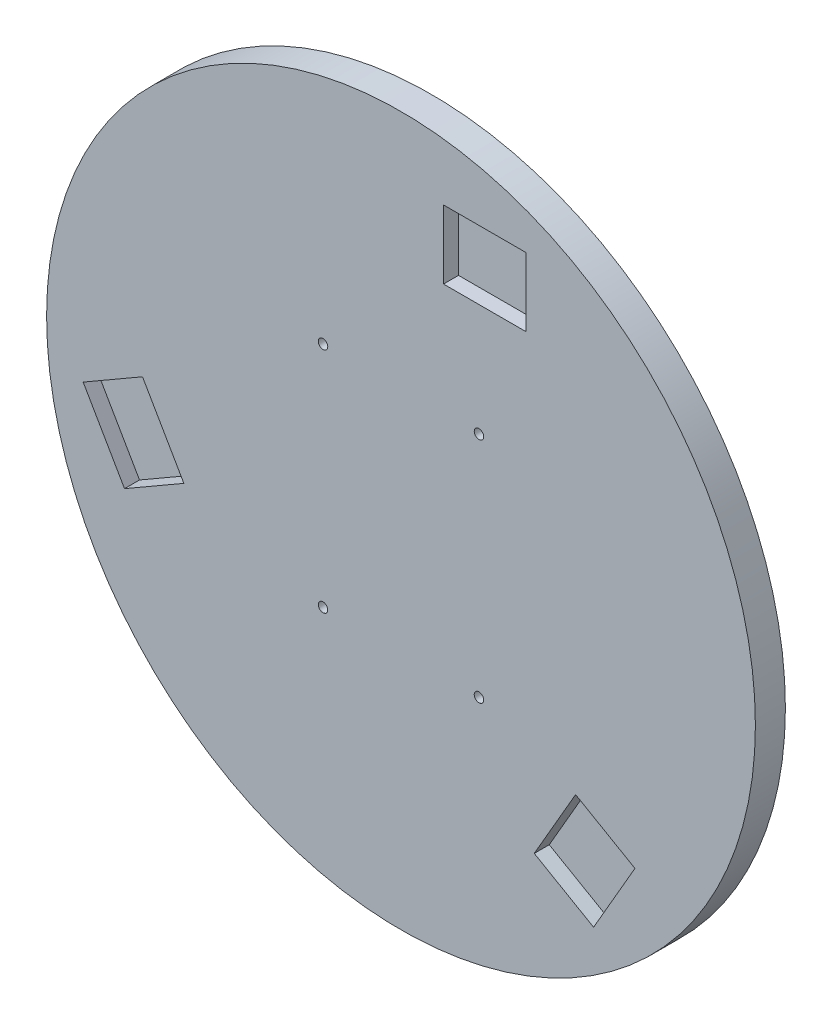
SolidWorks part; units mm, degrees
ref_plane "Plan de face" through (0, 0, 0) normal (0, 0, 1) x (1, 0, 0)
ref_plane "Plan de dessus" through (0, 0, 0) normal (0, 1, 0) x (1, 0, 0)
ref_plane "Plan de droite" through (0, 0, 0) normal (1, 0, 0) x (0, 0, -1)
sketch "Esquisse1" plane through (0, 0, 0) normal (0, 0, 1) x (1, 0, 0)
  circle A0 centre (0, 0) radius 150
  dimension "D1" = 300
extrude "Boss.-Extru.1" add sketch "Esquisse1" along normal blind 12.7
sketch "Esquisse2" plane through (0, 0, 12.7) normal (0, 0, 1) x (1, 0, 0)
  line L1 (-37.5, -52.75) -> (37.5, -52.75)
  line L2 (-37.5, -52.75) -> (-37.5, 52.75)
  line L3 (-37.5, 52.75) -> (37.5, 52.75)
  line L4 (37.5, -52.75) -> (37.5, 52.75)
  line L5 (-37.5, -52.75) -> (37.5, 52.75) construction
  line L6 (-37.5, 52.75) -> (37.5, -52.75) construction
  circle A0 centre (-33, 48.25) radius 2
  circle A1 centre (33, 48.25) radius 2
  circle A2 centre (-33, -48.25) radius 2
  circle A3 centre (33, -48.25) radius 2
  point P0 (0, 0)
  dimension "D3" = 4
  dimension "D5" = 4.5
  dimension "D6" = 4.5
  dimension "D7" = 4.5
  dimension "D8" = 4.5
  dimension "D9" = 4.5
  dimension "D10" = 4.5
  dimension "D11" = 4.5
  dimension "D1" = 105.5
  dimension "D2" = 75
  dimension "D4" = 4.5
extrude "Enlèv. mat.-Extru.1" cut sketch "Esquisse2" against normal blind 12.7 contours A0 | A1 | A3 | A2
sketch "Esquisse5" plane through (0, 0, 12.7) normal (0, 0, 1) x (1, 0, 0)
  line L0 (0, 133.3333) -> (-115.4701, -66.6667)
  line L1 (-115.4701, -66.6667) -> (115.4701, -66.6667)
  line L2 (115.4701, -66.6667) -> (0, 133.3333)
  line L3 (0, 133.3333) -> (-22, 95.2282)
  line L4 (-22, 95.2282) -> (22, 95.2282)
  line L5 (22, 95.2282) -> (0, 133.3333)
  line L6 (-115.4701, -66.6667) -> (-93.4701, -28.5615)
  line L7 (-93.4701, -28.5615) -> (-71.4701, -66.6667)
  line L8 (-71.4701, -66.6667) -> (-115.4701, -66.6667)
  line L9 (115.4701, -66.6667) -> (71.4701, -66.6667)
  line L10 (71.4701, -66.6667) -> (93.4701, -28.5615)
  line L11 (93.4701, -28.5615) -> (115.4701, -66.6667)
  line L12 (0, 0) -> (0, 133.3333) construction
  line L13 (-115.4701, -66.6667) -> (0, 0) construction
  line L14 (0, 0) -> (115.4701, -66.6667) construction
  dimension "D1" = 200
  dimension "D2" = 133.3333
  dimension "D3" = 44
sketch "Esquisse6" plane through (0, 0, 12.7) normal (0, 0, 1) x (1, 0, 0)
  line L0 (-22, 95.2282) -> (22, 95.2282) construction
  line L1 (18, 124.7282) -> (53, 124.7282)
  line L2 (18, 124.7282) -> (18, 95.7282)
  line L3 (18, 95.7282) -> (53, 95.7282)
  line L4 (53, 124.7282) -> (53, 95.7282)
  line L5 (73.9031, -63.4526) -> (56.4031, -93.7635)
  line L6 (56.4031, -93.7635) -> (81.5178, -108.2635)
  line L7 (81.5178, -108.2635) -> (99.0178, -77.9526)
  line L8 (99.0178, -77.9526) -> (73.9031, -63.4526)
  line L9 (71.4701, -66.6667) -> (93.4701, -28.5615) construction
  line L10 (-109.4031, -1.9648) -> (-91.9031, -32.2757)
  line L11 (-91.9031, -32.2757) -> (-117.0178, -46.7757)
  line L12 (-117.0178, -46.7757) -> (-134.5178, -16.4648)
  line L13 (-134.5178, -16.4648) -> (-109.4031, -1.9648)
  line L14 (-93.4701, -28.5615) -> (-71.4701, -66.6667) construction
  point P6 (0, 95.2282)
  point P7 (18, 110.2282)
  point P14 (82.4701, -47.6141)
  point P15 (86.4604, -70.7026)
  point P22 (-104.4604, -39.5257)
  point P23 (-82.4701, -47.6141)
  dimension "D1" = 29
  dimension "D2" = 35
  dimension "D3" = 18
  dimension "D4" = 15
  dimension "D5" = 29
  dimension "D6" = 35
  dimension "D7" = 18
  dimension "D8" = 15
  dimension "D9" = 35
  dimension "D10" = 29
  dimension "D11" = 15
  dimension "D12" = 18
extrude "Enlèv. mat.-Extru.2" cut sketch "Esquisse6" against normal blind 6.35
